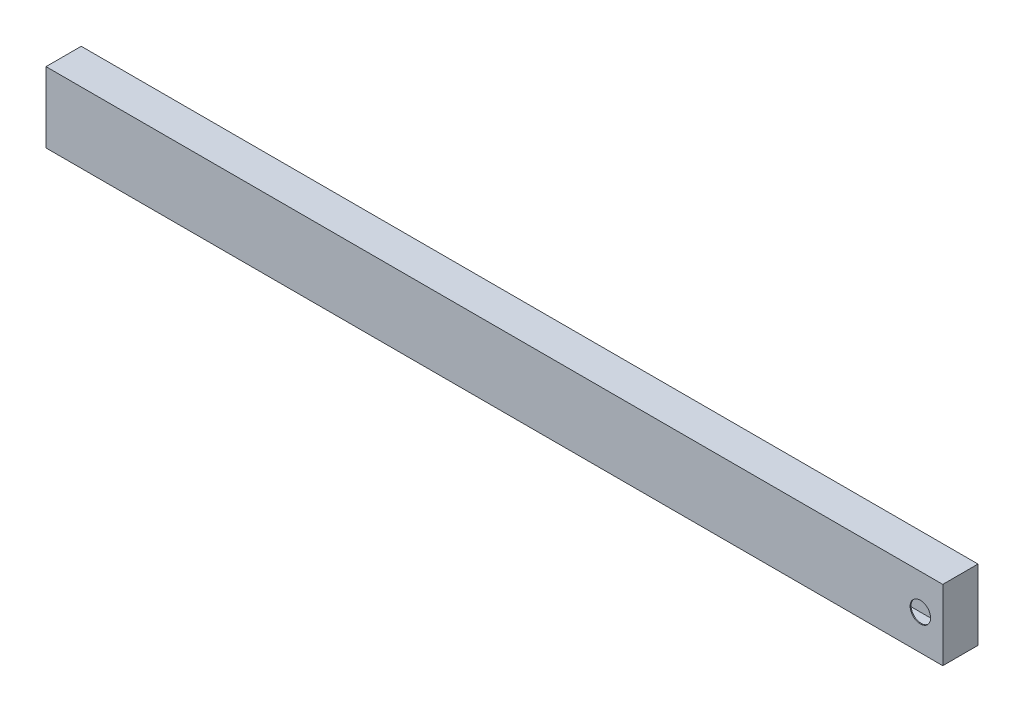
SolidWorks part; units mm, degrees
ref_plane "Спереди" through (0, 0, 0) normal (0, 0, 1) x (1, 0, 0)
ref_plane "Сверху" through (0, 0, 0) normal (0, 1, 0) x (1, 0, 0)
ref_plane "Справа" through (0, 0, 0) normal (1, 0, 0) x (0, 0, -1)
sketch "Эскиз1" plane through (0, 0, 0) normal (0, 1, 0) x (1, 0, 0)
  line L1 (0, 0) -> (-1400, 0)
  line L2 (0, 0) -> (0, 55)
  line L3 (0, 55) -> (-1400, 55)
  line L4 (-1400, 0) -> (-1400, 55)
  dimension "D1" = 1400
  dimension "D2" = 55
extrude "Бобышка-Вытянуть1" add sketch "Эскиз1" along normal blind 110
sketch "Эскиз2" plane through (0, 0, 0) normal (1, 0, 0) x (0, 0, -1)
  line L0 (55, 110) -> (55, 0) construction
  line L1 (53.5, 108.5) -> (1.5, 108.5)
  line L2 (53.5, 108.5) -> (53.5, 1.5)
  line L3 (53.5, 1.5) -> (1.5, 1.5)
  line L4 (1.5, 108.5) -> (1.5, 1.5)
  line L5 (0, 110) -> (55, 110) construction
  point P4 (53.5, 55)
  point P7 (55, 55)
  point P8 (27.5, 108.5)
  point P11 (27.5, 110)
  dimension "D1" = 107
  dimension "D2" = 52
sketch "Эскиз3" plane through (0, 0, -55) normal (0, 0, -1) x (-1, 0, 0)
  line L0 (0, 110) -> (0, 0) construction
  line L2 (1400, 110) -> (1400, 0) construction
  circle A0 centre (120, 55) radius 30
  circle A1 centre (225, 55) radius 30
  circle A2 centre (330, 55) radius 30
  circle A3 centre (435, 55) radius 30
  circle A4 centre (540, 55) radius 30
  circle A5 centre (645, 55) radius 30
  circle A6 centre (750, 55) radius 30
  circle A7 centre (855, 55) radius 30
  circle A8 centre (960, 55) radius 30
  circle A10 centre (1380, 55) radius 2.5
  circle A11 centre (1065, 55) radius 30
  circle A12 centre (1170, 55) radius 30
  circle A13 centre (1275, 55) radius 30
  point P5 (0, 55)
  dimension "D1" = 60
  dimension "D5" = 5
  dimension "D6" = 20
  dimension "D2" = 120
  dimension "D4" = 105
  dimension "D3" = 12
extrude "Вырез-Вытянуть1" cut sketch "Эскиз3" against normal blind 10
sketch "Эскиз4" plane through (0, 0, 0) normal (1, 0, 0) x (0, 0, -1)
  line L0 (55, 110) -> (55, 0) construction
  line L1 (53.5, 108.5) -> (1.5, 108.5)
  line L2 (53.5, 108.5) -> (53.5, 1.5)
  line L3 (53.5, 1.5) -> (1.5, 1.5)
  line L4 (1.5, 108.5) -> (1.5, 1.5)
  line L5 (0, 110) -> (55, 110) construction
  dimension "D1" = 107
  dimension "D2" = 52
  dimension "D3" = 1.5
  dimension "D4" = 1.5
extrude "Вырез-Вытянуть2" cut sketch "Эскиз4" against normal blind 1394 from offset 3 offset against normal yes
sketch "Эскиз5" plane through (0, 0, 0) normal (0, 0, 1) x (1, 0, 0)
  line L0 (-1400, 110) -> (-1400, 0) construction
  line L1 (0, 108.5) -> (0, 1.5) construction
  circle A0 centre (-35, 55) radius 16
  point P5 (-1400, 55)
  dimension "D1" = 32
  dimension "D2" = 35
extrude "Вырез-Вытянуть3" cut sketch "Эскиз5" against normal blind 10
